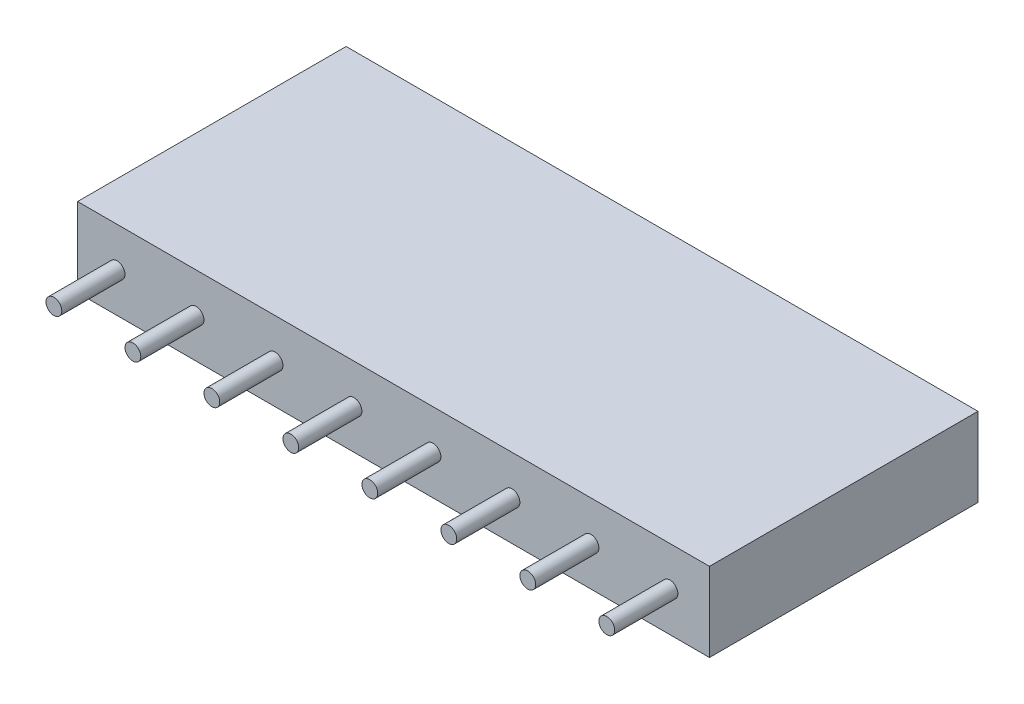
SolidWorks part; units mm, degrees
ref_plane "Plan de face" through (0, 0, 0) normal (0, 0, 1) x (1, 0, 0)
ref_plane "Plan de dessus" through (0, 0, 0) normal (0, 1, 0) x (1, 0, 0)
ref_plane "Plan de droite" through (0, 0, 0) normal (1, 0, 0) x (0, 0, -1)
sketch "Esquisse1" plane through (0, 0, 0) normal (0, 0, 1) x (1, 0, 0)
  line L1 (0, 0) -> (-2.5, 0)
  line L2 (0, 0) -> (0, 2.5)
  line L3 (0, 2.5) -> (-2.5, 2.5)
  line L4 (-2.5, 0) -> (-2.5, 2.5)
  dimension "D1" = 2.5
  dimension "D2" = 2.5
extrude "Boss.-Extru.1" add sketch "Esquisse1" along normal blind 8.5
sketch "Esquisse2" plane through (0, 0, 8.5) normal (0, 0, 1) x (1, 0, 0)
  line L0 (-2.5, 2.5) -> (0, 0) construction
  circle A0 centre (-1.25, 1.25) radius 0.25
  dimension "D1" = 0.5
extrude "Boss.-Extru.2" add sketch "Esquisse2" along normal blind 2
sketch "Esquisse3" plane through (0, 0, 0) normal (0, 0, -1) x (-1, 0, 0)
  line L0 (0, 2.5) -> (2.5, 0) construction
  circle A0 centre (1.25, 1.25) radius 0.25
  dimension "D1" = 0.5
extrude "Enlèv. mat.-Extru.2" cut sketch "Esquisse3" against normal blind 4
pattern_linear "Répétition linéaire1" count 8 spacing 2.5 along (-1, 0, 0) of "Boss.-Extru.1", "Enlèv. mat.-Extru.2", "Boss.-Extru.2"
